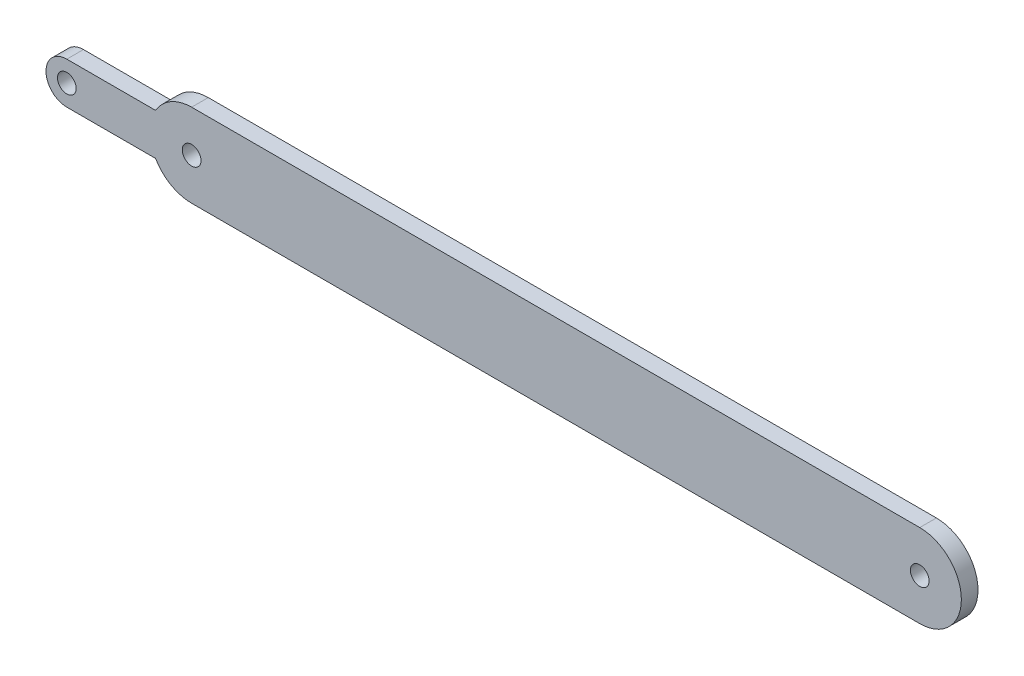
SolidWorks part; units mm, degrees
ref_plane "Front Plane" through (0, 0, 0) normal (0, 0, 1) x (1, 0, 0)
ref_plane "Top Plane" through (0, 0, 0) normal (0, 1, 0) x (1, 0, 0)
ref_plane "Right Plane" through (0, 0, 0) normal (1, 0, 0) x (0, 0, -1)
sketch "Sketch1" plane through (0, 0, 0) normal (0, 0, 1) x (1, 0, 0)
  line L1 (0, 10) -> (175, 10)
  line L2 (0, -10) -> (175, -10)
  line L3 (0, 0) -> (-30, 0) construction
  line L8 (-8.6603, -5) -> (-30, -5)
  line L9 (-8.6603, 5) -> (-30, 5)
  line L10 (175, 10) -> (175, -14.8875) construction
  arc A0 (0, 10) -> (-8.6603, 5) centre (0, 0) ccw
  arc A1 (175, -10) -> (175, 10) centre (175, 0) ccw
  arc A3 (-30, 5) -> (-30, -5) centre (-30, 0) ccw
  arc A4 (-8.6603, -5) -> (0, -10) centre (0, 0) ccw
  circle A5 centre (0, 0) radius 2.25
  circle A6 centre (-30, 0) radius 2.25
  circle A7 centre (175, 0) radius 2.25
  point P3 (50, 0)
  point P10 (-12.5, 0)
  dimension "D1" = 10
  dimension "D3" = 5
  dimension "D6" = 4.5
  dimension "D7" = 4.5
  dimension "D8" = 4.5
  dimension "D2" = 175
  dimension "D4" = 30
  dimension "D5" = 20
extrude "Boss-Extrude1" add sketch "Sketch1" along normal mid plane 4
